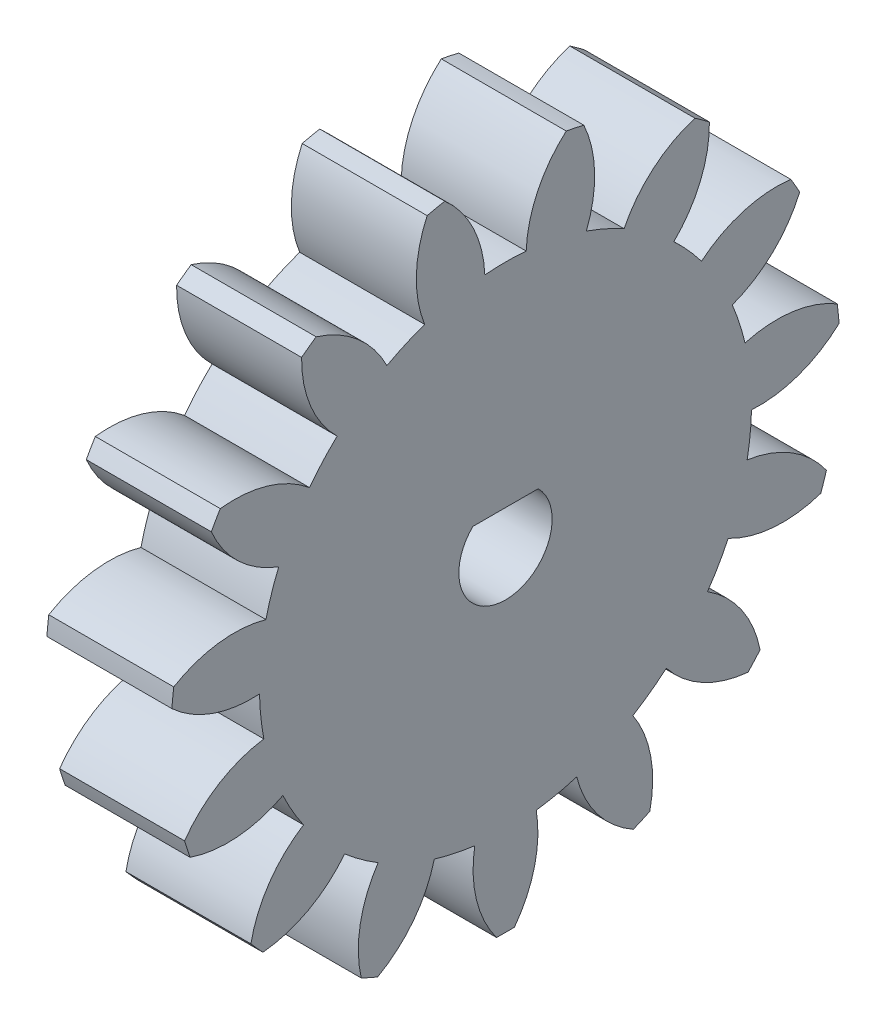
SolidWorks part; units mm, degrees
ref_plane "Plane1" through (0, 0, 0) normal (0, 0, 1) x (1, 0, 0)
ref_plane "Plane2" through (0, 0, 0) normal (0, 1, 0) x (1, 0, 0)
ref_plane "Plane3" through (0, 0, 0) normal (1, 0, 0) x (0, 0, -1)
sketch "HoldingSke" plane through (0, 0, 0) normal (0, 1, 0) x (1, 0, 0)
  line L0 (0, 0) -> (0.483, -0.1294)
  line L1 (-15, 0) -> (100, 0) construction
  line L2 (0, 0) -> (-2.1039, 2.3779)
  line L3 (0, 0) -> (-11.863, 4.5341)
  line L4 (0, 0) -> (8.3417, 2.2352)
  line L5 (0, 0) -> (-46.8476, -17.4728)
  line L6 (0, 0) -> (-5.2639, -3.5516)
  line L7 (-2.1039, 2.3779) -> (8.6586, 51.2059)
  line L8 (-76.2, 54.61) -> (-76.1, 54.61)
  line L9 (-71.009, 38.7566) -> (-53.1078, 45.2721)
  line L10 (-76.2, 71.12) -> (104.1128, 71.12)
  line L11 (0, 0) -> (-6.35, 0)
  line L12 (-76.2, 101.6) -> (-76.133, 101.6)
  line L13 (24.9733, 27.94) -> (52.9518, 28.4284)
  line L14 (24.9733, 27.94) -> (24.9743, 27.94)
  line L15 (24.9733, 27.94) -> (100.4006, 29.5858)
  line L16 (-63.627, -2) -> (-12.827, -2)
  circle A0 centre (0, 0) radius 0.4
  circle A1 centre (0, 0) radius 12.499
  circle A2 centre (0, 0) radius 37.5
  circle A3 centre (0, 0) radius 0.4
  dimension "MHD" = 24.998
  dimension "Hub_dia" = 75
  dimension "Bore" = 0.8
  dimension "MBD" = 0.8
  dimension "Num_teeth" = 15
  dimension "Pitch" = 0.5
  dimension "Overall_len" = 50
  dimension "Show_teeth" = 15
  dimension "Thickness" = 6.35
  dimension "OAL" = 50.0001
  dimension "T_dim" = 0.1
  dimension "Ap" = 20
  dimension "H" = 19.05
  dimension "Pitch_radius" = 180.3128
  dimension "Width" = 6.35
  dimension "Backlash" = 0.067
  dimension "Addendum_fac" = 1
  dimension "Dedendum_fac" = 1.25
  dimension "Clearance_fac" = 0.25
  dimension "Dedendum_add" = 0.001
  dimension "Module" = 2
sketch "BasProSke" plane through (0, 0, 0) normal (0, 1, 0) x (1, 0, 0)
  line L0 (-10, 0) -> (60, 0) construction
  line L1 (0, 0) -> (0, 17)
  line L2 (0, 0) -> (6.35, 0)
  line L3 (6.35, 0) -> (6.35, 17)
  line L4 (6.35, 17) -> (0, 17)
  dimension "Thickness" = 6.35
  dimension "Diameter" = 34
revolve "Base-Revolve" add sketch "BasProSke" angle 360 about L0
sketch "TooCutSke" plane through (0, 0, 0) normal (1, 0, 0) x (0, 0, -1)
  line L1 (0, 0) -> (0, 107) construction
  line L2 (0, 0) -> (-1.6851, 14.905) construction
  line L3 (0, 0) -> (-6.2081, 29.2069) construction
  line L4 (-1.6851, 14.905) -> (-3.1041, 14.6034) construction
  arc A0 (1.0501, 12.4548) -> (-1.0501, 12.4548) centre (0, 0) ccw
  arc A1 (3.1109, 16.7388) -> (-3.1109, 16.7388) centre (0, 0) ccw
  circle A2 centre (0, 0) radius 15 construction
  circle A3 centre (0, 0) radius 14.0954 construction
  arc A4 (-1.0501, 12.4548) -> (-3.1109, 16.7388) centre (-7.045, 12.2085) ccw
  arc A5 (3.1109, 16.7388) -> (1.0501, 12.4548) centre (7.045, 12.2085) ccw
  dimension "Root_dia" = 24.998
  dimension "Overcut_dia" = 34.0508
  dimension "Pitch_dia" = 30
  dimension "Base_dia" = 28.1908
  dimension "Flank_rad" = 6
  dimension "Half_ang" = 12
  dimension "Half_CT" = 1.4507
extrude "ToothCut" cut sketch "TooCutSke" along normal through all
fillet "Breaks" [suppressed] radius 0.04
fillet "RootFillets" [suppressed] radius 0.501
pattern_circular "TeethCuts" count 15 over 360 about axis through (0, 0, 0) along (1, 0, 0) of "ToothCut", "RootFillets", "Breaks"
sketch "HubNeaOneSke" plane through (0, 0, 0) normal (-1, 0, 0) x (0, 0, 1)
  circle A0 centre (0, 0) radius 12.499
  dimension "Diameter" = 24.998
extrude "HubNearOne" [suppressed] add sketch "HubNeaOneSke" along normal blind 43.6501
sketch "HubNeaBotSke" plane through (0, 0, 0) normal (-1, 0, 0) x (0, 0, 1)
  circle A0 centre (0, 0) radius 12.499
  dimension "Diameter" = 24.998
extrude "HubNearBoth" [suppressed] add sketch "HubNeaBotSke" along normal blind 21.825
ref_plane "FarPln" through (6.35, 0, 0) normal (1, 0, 0) x (0, 0, -1)
sketch "HubFarSke" plane through (6.35, 0, 0) normal (1, 0, 0) x (0, 0, -1)
  circle A0 centre (0, 0) radius 12.499
  dimension "Diameter" = 24.998
extrude "HubFar" [suppressed] add sketch "HubFarSke" along normal blind 21.825
sketch "BorSke" plane through (0, 0, 0) normal (1, 0, 0) x (0, 0, -1)
  circle A0 centre (0, 0) radius 0.4
  dimension "Diameter" = 0.8
extrude "Bore" cut sketch "BorSke" along normal mid plane 100.0001
sketch "KeySke" plane through (0, 0, 0) normal (1, 0, 0) x (0, 0, -1)
  line L0 (-0.05, 0) -> (-0.05, 0.5)
  line L1 (-0.05, 0.5) -> (0.05, 0.5)
  line L2 (0.05, 0.5) -> (0.05, 0)
  line L3 (0, 0) -> (0, 34) construction
  line L4 (-0.05, 0) -> (0.05, 0)
  dimension "Offset" = 0.5
  dimension "Width" = 0.1
extrude "Keyway" [suppressed] cut sketch "KeySke" along normal mid plane 100.0001
pattern_circular "Keyway2" [suppressed] count 2 every 90 about axis through (-10, 0, 0) along (1, 0, 0)
sketch "Sketch1" plane through (0, 0, 0) normal (-1, 0, 0) x (0, 0, 1)
  line L0 (-1.6599, 1.6916) -> (1.6599, 1.6916)
  circle A0 centre (0, 0) radius 2.37
  dimension "D1" = 4.74
  dimension "D2" = 1.6916
extrude "Cut-Extrude1" cut sketch "Sketch1" against normal through all contours L0 A0
equation "' \"Module@HoldingSke\" = 6.35"
equation "' \"Num_teeth@HoldingSke\" = 12"
equation "' \"Ap@HoldingSke\" =  20"
equation "' \"Ap@HoldingSke\" = 20"
equation "' \"Width@HoldingSke\" = 0.5 * 25.4"
equation "' \"Hub_dia@HoldingSke\"= 1 * 25.4"
equation "' \"Hub_dia@HoldingSke\" = 1 * 25.4"
equation "' \"Overall_len@HoldingSke\" = 1.0 * 25.4"
equation "' \"Bore@HoldingSke\" = 0.75 * 25.4"
equation "' \"T_dim@HoldingSke\" = 0.1 * 25.4"
equation "' \"Width@KeySke\" = 0.25 * 25.4"
equation "' \"Show_teeth@HoldingSke\" = 13"
equation "' \"Backlash@HoldingSke\" = 0.009 * 25.4"
equation "' \"Addendum_fac@HoldingSke\" = 1.0"
equation "' \"Dedendum_fac@HoldingSke\" = 1.25"
equation "' \"Dedendum_add@HoldingSke\" = 0.00005 * 25.4"
equation "' \"Clearance_fac@HoldingSke\" = 0.25"
equation "\"Pitch@HoldingSke\" = 1 / \"Module@HoldingSke\""
equation "\"Overcut_dia@TooCutSke\" = (\"Num_teeth@HoldingSke\" + 2 * \"Addendum_fac@HoldingSke\") / \"Pitch@HoldingSke\" + 0.002 * 25.4"
equation "\"Pitch_dia@TooCutSke\" = \"Num_teeth@HoldingSke\" / \"Pitch@HoldingSke\""
equation "\"Base_dia@TooCutSke\" = \"Num_teeth@HoldingSke\" / \"Pitch@HoldingSke\" * cos((\"Ap@HoldingSke\"  * 3.14159265 / 180))"
equation "\"Root_dia@TooCutSke\" = (\"Num_teeth@HoldingSke\" + 2) / \"Pitch@HoldingSke\" - 2 * (\"Addendum_fac@HoldingSke\" + \"Dedendum_fac@HoldingSke\") / \"Pitch@HoldingSke\" - \"Dedendum_add@HoldingSke\" * 2"
equation "\"Half_ang@TooCutSke\" = 180 / \"Num_teeth@HoldingSke\""
equation "\"Half_CT@TooCutSke\" = \"Num_teeth@HoldingSke\" / \"Pitch@HoldingSke\" * sin((3.14159265 / 2 / \"Num_teeth@HoldingSke\")) / 2 - 7 * \"Backlash@HoldingSke\" / 4"
equation "\"Flank_rad@TooCutSke\" = \"Num_teeth@HoldingSke\" / \"Pitch@HoldingSke\" / 5"
equation "\"Radius@RootFillets\" = \"Clearance_fac@HoldingSke\" / \"Pitch@HoldingSke\" + \"Dedendum_add@HoldingSke\""
equation "\"Break_rad@Breaks\" = 0.02 / \"Pitch@HoldingSke\""
equation "\"Thickness@HoldingSke\" = \"Width@HoldingSke\""
equation "\"OAL@HoldingSke\" = \"Thickness@HoldingSke\""
equation "\"MHD@HoldingSke\" = (\"Num_teeth@HoldingSke\" + 2) / \"Pitch@HoldingSke\" - 2 * (\"Addendum_fac@HoldingSke\" + \"Dedendum_fac@HoldingSke\")  / \"Pitch@HoldingSke\" - \"Dedendum_add@HoldingSke\" * 2"
equation "\"MBD@HoldingSke\" = (\"Num_teeth@HoldingSke\" + 2) / \"Pitch@HoldingSke\" - 2 * (\"Addendum_fac@HoldingSke\" + \"Dedendum_fac@HoldingSke\")  / \"Pitch@HoldingSke\" - \"Dedendum_add@HoldingSke\" * 2 - 0.002 * 25.4"
equation "\"MHD@HoldingSke\" = ((sgn( \"MHD@HoldingSke\" - \"Hub_dia@HoldingSke\" )-1)*( \"MHD@HoldingSke\" - \"Hub_dia@HoldingSke\" ))/-2+ \"Hub_dia@HoldingSke\""
equation "\"MBD@HoldingSke\" = ((sgn( \"MBD@HoldingSke\" - \"Bore@HoldingSke\" )-1)*( \"MBD@HoldingSke\" - \"Bore@HoldingSke\" ))/-2+ \"Bore@HoldingSke\""
equation "\"OAL@HoldingSke\" = ((sgn( \"OAL@HoldingSke\" - \"Overall_len@HoldingSke\" )+1)*( \"OAL@HoldingSke\" - \"Overall_len@HoldingSke\" ))/2 + \"Overall_len@HoldingSke\" + 0.000002 * 25.4"
equation "\"Num_teeth@TeethCuts\" = int( \"Show_teeth@HoldingSke\" ) + 1"
equation "\"Num_teeth@TeethCuts\" = ((sgn( \"Num_teeth@TeethCuts\" - \"Num_teeth@HoldingSke\" )-1)*( \"Num_teeth@TeethCuts\" - \"Num_teeth@HoldingSke\" ))/-2+ \"Num_teeth@HoldingSke\""
equation "\"Num_teeth@TeethCuts\" = ((sgn( \"Num_teeth@TeethCuts\" - 2.0)+1)*( \"Num_teeth@TeethCuts\" - 2.0))/2 +2.0"
equation "\"Angle@TeethCuts\" = 360.0 / \"Num_teeth@HoldingSke\""
equation "\"Diameter@BasProSke\" = (\"Num_teeth@HoldingSke\" + 2 * \"Addendum_fac@HoldingSke\") / \"Pitch@HoldingSke\""
equation "\"Thickness@BasProSke\"  = \"Thickness@HoldingSke\""
equation "' \"Fillet_rad@BasProSke\" =  \"Thickness@HoldingSke\" * 0.05"
equation "' \"Fillet_rad@BasProSke\" = \"Thickness@HoldingSke\" * 0.05"
equation "\"MHD@HoldingSke\" = ((sgn( \"MHD@HoldingSke\" - \"Root_dia@TooCutSke\" )-1)*( \"MHD@HoldingSke\" - \"Root_dia@TooCutSke\" ))/-2+ \"Root_dia@TooCutSke\""
equation "\"Diameter@HubNeaOneSke\" = \"MHD@HoldingSke\""
equation "\"Length@HubNearOne\" = \"OAL@HoldingSke\" - \"Thickness@BasProSke\""
equation "\"Diameter@HubNeaBotSke\" = \"MHD@HoldingSke\""
equation "\"Length@HubNearBoth\" = ( \"OAL@HoldingSke\" - \"Thickness@BasProSke\" ) / 2.0"
equation "\"Thickness@FarPln\" = \"Thickness@BasProSke\""
equation "\"Diameter@HubFarSke\" = \"MHD@HoldingSke\""
equation "\"Length@HubFar\" = ( \"OAL@HoldingSke\" - \"Thickness@BasProSke\" ) / 2.0"
equation "\"Diameter@BorSke\" = \"MBD@HoldingSke\""
equation "\"D1@Bore\" = \"OAL@HoldingSke\" * 2.0"
equation "\"D1@Keyway\" = \"OAL@HoldingSke\" * 2.0"
equation "\"Offset@KeySke\" = \"T_dim@HoldingSke\" + \"MBD@HoldingSke\" / 2.0"
